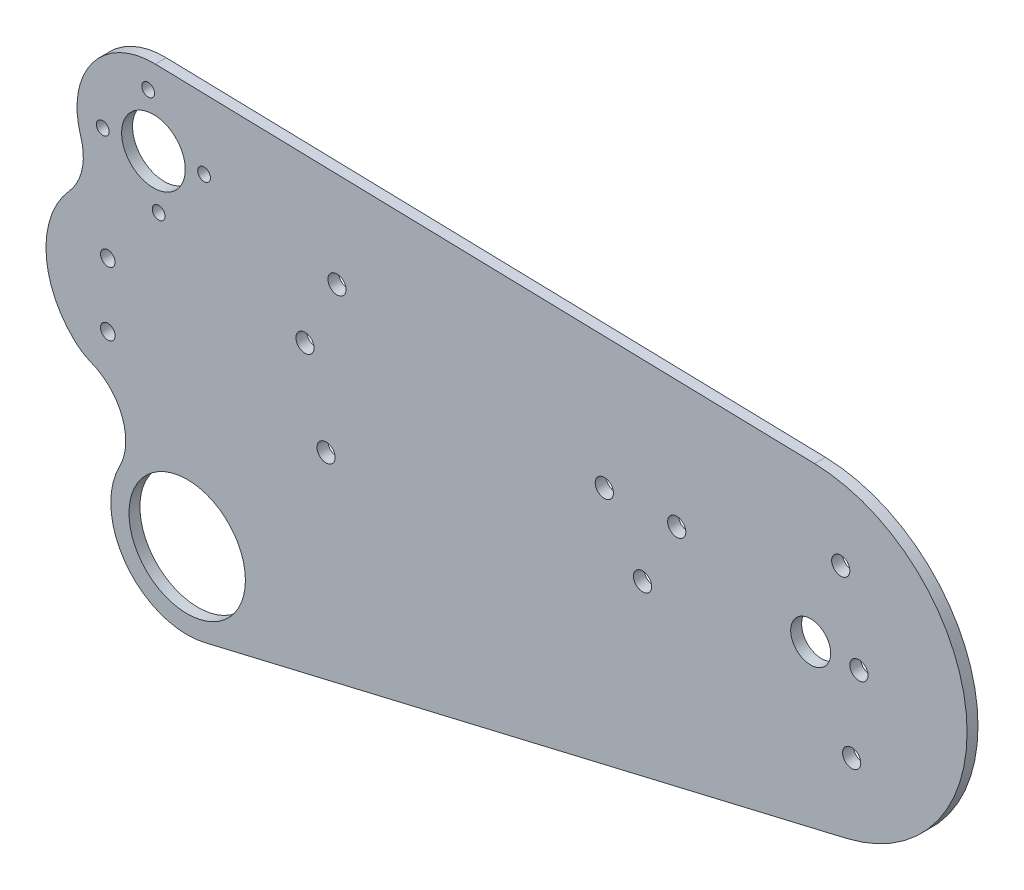
SolidWorks part; units mm, degrees
ref_plane "Front Plane" through (0, 0, 0) normal (0, 0, 1) x (1, 0, 0)
ref_plane "Top Plane" through (0, 0, 0) normal (0, 1, 0) x (1, 0, 0)
ref_plane "Right Plane" through (0, 0, 0) normal (1, 0, 0) x (0, 0, -1)
sketch "Sketch1" plane through (0, 0, 0) normal (0, 0, 1) x (1, 0, 0)
  line L0 (111.6392, -33.5) -> (-127.2004, -33.5) construction
  line L1 (-115.2419, 47.4935) -> (103.8038, 42.0468)
  line L2 (-117.9482, 47.5608) -> (-104.2948, -84.0806) construction
  line L3 (-101.6599, -83.4593) -> (111.6055, -33.1747)
  line L4 (103.8038, 42.0468) -> (111.6055, -33.1747)
  line L5 (-111.1215, -18.2599) -> (107.7046, 4.436) construction
  line L6 (91, -33.5) -> (-88.5, -33.5) construction
  line L7 (-97.4673, 5.5) -> (-145.3054, 5.5) construction
  line L8 (-128.3, -14) -> (-145.3054, -14) construction
  line L9 (-128.3, 5.5) -> (-128.3, -33.5) construction
  line L10 (-145.3054, 5.5) -> (-145.3054, -33.5) construction
  line L11 (64.9341, 33.5) -> (64.9341, -33.5) construction
  line L13 (-91.5, 33.5) -> (88, 33.5) construction
  circle A0 centre (64.9341, 0) radius 5.5
  circle A1 centre (-115.7639, 26.5) radius 14 construction
  circle A2 centre (-106.4792, -63.0198) radius 14 construction
  arc A3 (-91.5, 33.5) -> (-88.5, -33.5) centre (-18.0922, 3.2198) ccw construction
  circle A4 centre (-68.3, -21.5) radius 2.5
  circle A5 centre (-68.3, -21.5) radius 2.5 construction
  circle A6 centre (-128.3, -5.25) radius 2
  circle A7 centre (-128.3, -22.75) radius 2
  arc A8 (-138.8579, 5.5) -> (-137.5429, -29.3643) centre (-120.3054, -11.2571) ccw
  arc A9 (-137.5429, -29.3643) -> (-127.2004, -33.5) centre (-127.2004, -18.5) ccw
  circle A10 centre (-115.7639, 26.5) radius 21
  arc A11 (-91.5, 33.5) -> (-96.4806, 15.9028) centre (-18.0922, 3.2198) ccw construction
  circle A12 centre (-106.4792, -63.0198) radius 21
  arc A13 (89.5659, -36.5286) -> (83.5219, 40.5604) centre (22.6589, -2.9929) ccw construction
  arc A14 (91, -33.5) -> (88, 33.5) centre (22.6589, -2.9929) ccw construction
  arc A15 (83.5219, 40.5604) -> (79.58, 42.6491) centre (79.4557, 37.6507) ccw
  arc A16 (86.2434, -39.1547) -> (89.5659, -36.5286) centre (85.096, -34.2882) ccw
  arc A17 (-125.0887, -53.2891) -> (-132.7908, -32.4193) centre (-138.3812, -46.3386) ccw
  arc A18 (-138.8902, 5.4642) -> (-135.759, 20.0816) centre (-150.0412, 15.497) ccw
  circle A19 centre (-74.1, 1.7) radius 2.5
  circle A20 centre (-65.3, 20) radius 2.5
  circle A21 centre (8.2, 8.3) radius 2.5
  circle A22 centre (28.1, 9) radius 2.5
  circle A23 centre (18.7, -8.7) radius 2.5
  circle A25 centre (78.2, -0.1) radius 2.5
  circle A26 centre (76.2, -22) radius 2.5
  circle A27 centre (73.2, 22.3) radius 2.5
  circle A28 centre (73.2, 22.3) radius 2.5 construction
  circle A29 centre (78.2, -0.1) radius 2.5 construction
  circle A30 centre (28.1, 9) radius 2.5 construction
  circle A31 centre (8.2, 8.3) radius 2.5 construction
  circle A32 centre (18.7, -8.7) radius 2.5 construction
  circle A33 centre (76.2, -22) radius 2.5 construction
  circle A34 centre (-74.1, 1.7) radius 2.5 construction
  circle A35 centre (-65.3, 20) radius 2.5 construction
  circle A36 centre (-117.2082, 40.4253) radius 1.75
  circle A37 centre (-101.8386, 27.9443) radius 1.75
  circle A38 centre (-114.3196, 12.5747) radius 1.75
  circle A39 centre (-129.6892, 25.0557) radius 1.75
  circle A40 centre (-107.9235, -49.0945) radius 1.75
  circle A41 centre (-92.5539, -61.5755) radius 1.75
  circle A42 centre (-105.0349, -76.9451) radius 1.75
  circle A43 centre (-120.4045, -64.4641) radius 1.75
  circle A44 centre (64.9341, 0) radius 35 construction
  circle A45 centre (64.9341, 0) radius 43
  circle A49 centre (-106.4792, -63.0198) radius 16
  circle A50 centre (-115.7639, 26.5) radius 16 construction
  circle A51 centre (-115.7639, 26.5) radius 8.75
  circle A52 centre (-106.4792, -63.0198) radius 8.75
  point P52 (107.7046, 4.436)
  point P109 (-115.7639, 26.5)
  point P118 (-106.4792, -63.0198)
  dimension "D5" = 4
  dimension "D6" = 25
  dimension "D9" = 15
  dimension "D13" = 10
  dimension "D14" = 28
  dimension "D11" = 42
  dimension "D15" = 3.5
  dimension "D12" = 70
  dimension "D19" = 11
  dimension "D20" = 17.5
  dimension "D22" = 32
  dimension "D2" = 39
  dimension "D3" = 60
  dimension "D4" = 17.5
  dimension "D7" = 14
  dimension "D8" = 10
  dimension "D10" = 90
  dimension "D21" = 220
  dimension "D18" = 8
  dimension "D16" = 4
  dimension "D17" = 4
extrude "Boss-Extrude1" add sketch "Sketch1" along normal blind 3
